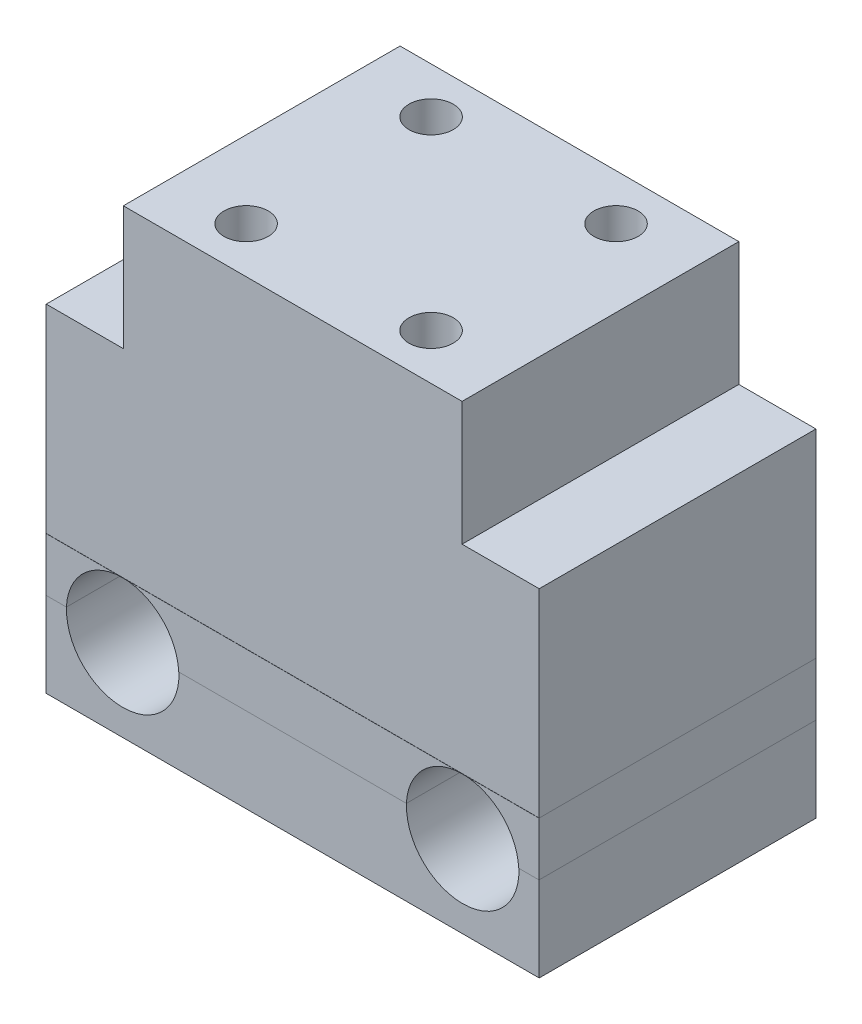
SolidWorks part; units mm, degrees
ref_plane "Front Plane" through (0, 0, 0) normal (0, 0, 1) x (1, 0, 0)
ref_plane "Top Plane" through (0, 0, 0) normal (0, 1, 0) x (1, 0, 0)
ref_plane "Right Plane" through (0, 0, 0) normal (1, 0, 0) x (0, 0, -1)
sketch "Sketch1" plane through (0, 0, 0) normal (0, 1, 0) x (1, 0, 0)
  line L1 (12.654, -10.3378) -> (-12.654, -10.3378)
  line L2 (12.654, -10.3378) -> (12.654, 10.3378)
  line L3 (12.654, 10.3378) -> (-12.654, 10.3378)
  line L4 (-12.654, -10.3378) -> (-12.654, 10.3378)
  line L5 (12.654, -10.3378) -> (-12.654, 10.3378) construction
  line L6 (12.654, 10.3378) -> (-12.654, -10.3378) construction
  point P0 (0, 0)
  dimension "D1" = 25.308
  dimension "D2" = 20.6756
extrude "Boss-Extrude1" add sketch "Sketch1" along normal blind 9.2424
sketch "Sketch3" plane through (0, 0, 0) normal (0, -1, 0) x (-1, 0, 0)
  line L1 (-18.415, 10.3378) -> (18.415, 10.3378)
  line L2 (-18.415, 10.3378) -> (-18.415, -10.3378)
  line L3 (-18.415, -10.3378) -> (18.415, -10.3378)
  line L4 (18.415, 10.3378) -> (18.415, -10.3378)
  line L5 (-18.415, 10.3378) -> (18.415, -10.3378) construction
  line L6 (-18.415, -10.3378) -> (18.415, 10.3378) construction
  point P0 (0, 0)
  dimension "D1" = 36.83
extrude "Boss-Extrude2" add sketch "Sketch3" along normal blind 14.8368
sketch "Sketch4" plane through (0, 9.2424, 0) normal (0, 1, 0) x (1, 0, 0)
  line L0 (0, 10.3378) -> (0, -10.3378) construction
  line L1 (12.654, 10.3378) -> (-12.654, 10.3378) construction
  line L2 (-12.654, -10.3378) -> (12.654, -10.3378) construction
  line L3 (12.654, 0) -> (-12.654, 0) construction
  line L4 (12.654, -10.3378) -> (12.654, 10.3378) construction
  line L5 (-12.654, 10.3378) -> (-12.654, -10.3378) construction
  line L6 (6.9088, -6.9088) -> (-6.9088, -6.9088) construction
  line L7 (6.9088, 6.9088) -> (-6.9088, 6.9088) construction
  circle A0 centre (-6.9088, -6.9088) radius 1.6526
  circle A1 centre (6.9088, -6.9088) radius 1.6526
  circle A2 centre (6.9088, 6.9088) radius 1.6526
  circle A3 centre (-6.9088, 6.9088) radius 1.6526
  point P15 (0, -6.9088)
  point P21 (0, 6.9088)
  dimension "D3" = 3.3052
  dimension "D1" = 13.8176
  dimension "D2" = 6.9088
extrude "Cut-Extrude2" cut sketch "Sketch4" against normal blind 11.1125
sketch "Sketch5" plane through (0, -14.8368, 0) normal (0, -1, 0) x (-1, 0, 0)
  line L0 (-18.415, 0.8128) -> (18.415, 0.8128) construction
  line L1 (-18.415, 10.3378) -> (-18.415, -10.3378) construction
  line L2 (18.415, -10.3378) -> (18.415, 10.3378) construction
  line L3 (18.415, 10.3378) -> (-18.415, 10.3378) construction
  line L4 (0, -10.3378) -> (0, 10.3378) construction
  line L5 (-18.415, -10.3378) -> (18.415, -10.3378) construction
  circle A0 centre (-12.7, 0.8128) radius 1.7526
  circle A1 centre (12.7, 0.8128) radius 1.7526
  dimension "D2" = 3.5052
  dimension "D1" = 9.525
  dimension "D3" = 12.7
extrude "Cut-Extrude3" cut sketch "Sketch5" against normal blind 7.9375
sketch "Sketch6" plane through (0, 0, -10.3378) normal (0, 0, -1) x (-1, 0, 0)
  line L0 (0, -14.8368) -> (0, 9.2424) construction
  line L1 (18.415, -14.8368) -> (-18.415, -14.8368) construction
  line L2 (-12.654, 9.2424) -> (12.654, 9.2424) construction
  line L3 (-12.7, -14.8368) -> (-12.7, 9.2424) construction
  line L4 (-18.415, -14.8368) -> (0, -14.8368)
  line L5 (-18.415, -14.8368) -> (-18.415, -18.8368)
  line L6 (-18.415, -18.8368) -> (-16.8952, -18.8368)
  line L7 (-18.415, -19.0368) -> (0, -19.0368) construction
  line L8 (-8.5048, -18.8368) -> (8.5048, -18.8368)
  line L9 (18.415, -18.8368) -> (16.8952, -18.8368)
  line L10 (18.415, -14.8368) -> (18.415, -18.8368)
  line L11 (0, -14.8368) -> (12.7, -14.8368)
  arc A0 (-8.5048, -18.8368) -> (-16.8952, -18.8368) centre (-12.7, -19.0368) ccw
  arc A1 (8.5048, -18.8368) -> (16.8952, -18.8368) centre (12.7, -19.0368) cw
  point P18 (0, -18.8368)
  line M10 (-18.415, -14.8368) -> (18.415, -14.8368)
  dimension "D2" = 8.4
  dimension "D1" = 12.7
  dimension "D3" = 0.2
extrude "Boss-Extrude7" add sketch "Sketch6" against normal blind 20.6883 separate body contours L8 A1 L4 A0 M10 | A0 L5 L6 M10 | A1 L9 L10 M10
ref_plane "Plane1" through (0, -14.8368, 0) normal (0, 1, 0) x (1, 0, 0)
sketch "Sketch8" plane through (0, -18.8368, 0) normal (0, -1, 0) x (-1, 0, 0)
  line L0 (0, 10.3378) -> (0, -8.109) construction
  line L1 (-8.5048, 10.3378) -> (8.5048, 10.3378) construction
  line L3 (-8.5048, -0.0064) -> (8.5048, -0.0064) construction
  line L4 (-8.5048, -10.3505) -> (-8.5048, 10.3378) construction
  line L5 (8.5048, -10.3505) -> (8.5048, 10.3378) construction
  circle A0 centre (0, 6.3436) radius 1.7526
  circle A1 centre (0, -6.3564) radius 1.7526
  dimension "D1" = 3.5052
  dimension "D2" = 6.35
sketch "Sketch10" plane through (0, 0, -10.3378) normal (0, 0, -1) x (-1, 0, 0)
  line L0 (-18.415, -18.8368) -> (-18.415, -25.1868)
  line L1 (-18.415, -25.1868) -> (18.415, -25.1868)
  line L2 (-18.415, -18.8368) -> (-16.8952, -18.8368)
  line L3 (-8.5048, -18.8368) -> (8.5048, -18.8368)
  line L4 (-1.7526, -18.8368) -> (1.7526, -18.8368) construction
  line L5 (0, 9.2424) -> (0, -18.8368) construction
  line L6 (-12.654, 9.2424) -> (12.654, 9.2424) construction
  line L7 (18.415, -18.8368) -> (16.8952, -18.8368)
  line L8 (18.415, -18.8368) -> (18.415, -25.1868)
  arc A0 (-16.8952, -18.8368) -> (-8.5048, -18.8368) centre (-12.7, -19.0368) ccw
  arc A1 (16.8952, -18.8368) -> (8.5048, -18.8368) centre (12.7, -19.0368) cw
  point P18 (0, -25.1868)
  dimension "D1" = 6.35
extrude "Boss-Extrude9" add sketch "Sketch10" against normal up to surface (20.6756 mm away) separate body up to face at (0.7201, -0.2433, 10.3378)
sketch "Sketch9" plane through (0, -14.8368, 0) normal (0, 1, 0) x (1, 0, 0)
  line L0 (-12.7, 10.3378) -> (-12.7, -0.8398) construction
  line L1 (0, 10.3378) -> (0, -10.6643) construction
  line L2 (12.7, 10.3378) -> (-12.7, 10.3378) construction
  circle A0 centre (-12.7, 0.8128) radius 1.6526
  circle A1 centre (12.7, 0.8128) radius 1.6526
  dimension "D1" = 3.3052
  dimension "D2" = 9.525
extrude "Cut-Extrude5" cut sketch "Sketch9" against normal through all and the other way blind 6.35
chamfer "Chamfer1" distance 0.2 angle 45 2 edges at (-12.7, -25.1868, 0.8398) (12.7, -25.1868, -2.4654)
